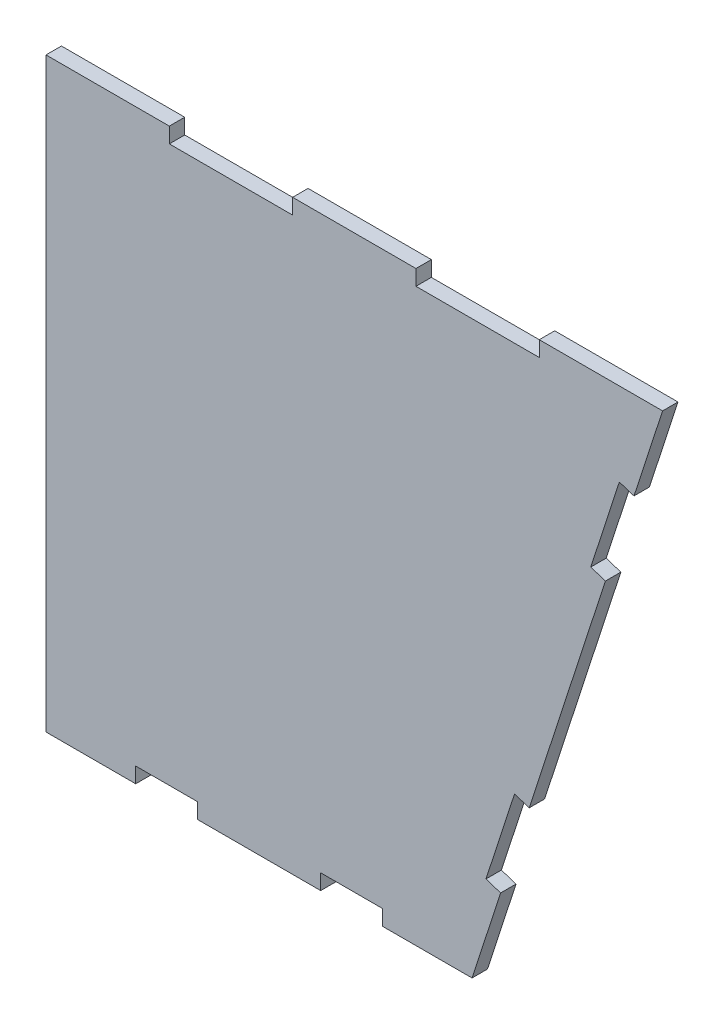
SolidWorks part; units mm, degrees
ref_plane "Front Plane" through (0, 0, 0) normal (0, 0, 1) x (1, 0, 0)
ref_plane "Top Plane" through (0, 0, 0) normal (0, 1, 0) x (1, 0, 0)
ref_plane "Right Plane" through (0, 0, 0) normal (1, 0, 0) x (0, 0, -1)
sketch "Sketch1" plane through (0, 0, 0) normal (0, 0, 1) x (1, 0, 0)
  line L0 (0, 0) -> (5.8868, 18.1176)
  line L1 (39.2452, 120.7842) -> (13.8452, 120.7842)
  line L2 (-87.7548, 120.7842) -> (-87.7548, 0)
  line L3 (-87.7548, 0) -> (-69.2774, 0)
  line L4 (33.3584, 102.6666) -> (30.3388, 103.6477)
  line L5 (30.3388, 103.6477) -> (24.452, 85.5301)
  line L6 (24.452, 85.5301) -> (27.4716, 84.5489)
  line L7 (19.6226, 60.3921) -> (-40.3388, 79.8747) construction
  line L8 (33.3584, 102.6666) -> (39.2452, 120.7842)
  line L9 (8.7539, 37.2164) -> (11.7735, 36.2353)
  line L10 (2.8672, 19.0988) -> (8.7539, 37.2164)
  line L11 (5.8868, 18.1176) -> (2.8672, 19.0988)
  line L12 (11.7735, 36.2353) -> (27.4716, 84.5489)
  line L13 (-24.2548, 120.7842) -> (-24.2548, 85.5301) construction
  line L14 (-87.7548, 60.3921) -> (-47.3707, 60.3921) construction
  line L15 (-43.8774, -0.5899) -> (-43.8774, 24.117) construction
  line L16 (-62.3548, 120.7842) -> (-62.3548, 117.6092)
  line L17 (-62.3548, 117.6092) -> (-36.9548, 117.6092)
  line L18 (-36.9548, 117.6092) -> (-36.9548, 120.7842)
  line L19 (-62.3548, 120.7842) -> (-87.7548, 120.7842)
  line L20 (-87.7548, 126.9801) -> (39.2452, 126.9801) construction
  line L21 (13.8452, 120.7842) -> (13.8452, 117.6092)
  line L22 (13.8452, 117.6092) -> (-11.5548, 117.6092)
  line L23 (-11.5548, 117.6092) -> (-11.5548, 120.7842)
  line L24 (-11.5548, 120.7842) -> (-36.9548, 120.7842)
  line L25 (-69.2774, 0) -> (-69.2774, 3.175)
  line L26 (-69.2774, 3.175) -> (-56.5774, 3.175)
  line L27 (-56.5774, 3.175) -> (-56.5774, 0)
  line L28 (-56.5774, 0) -> (-31.1774, 0)
  line L29 (-18.4774, 0) -> (-18.4774, 3.175)
  line L30 (-18.4774, 3.175) -> (-31.1774, 3.175)
  line L31 (-31.1774, 3.175) -> (-31.1774, 0)
  line L32 (-18.4774, 0) -> (0, 0)
  point P27 (-24.2548, 126.9801)
  point P40 (0, 0)
  dimension "D1" = 108
  dimension "D2" = 127
  dimension "D3" = 127
  dimension "D4" = 25.4
  dimension "D5" = 19.05
  dimension "D6" = 3.175
  dimension "D7" = 3.175
  dimension "D8" = 25.4
  dimension "D9" = 12.7
  dimension "D10" = 3.175
  dimension "D11" = 12.7
  dimension "D12" = 12.7
extrude "Boss-Extrude1" add sketch "Sketch1" along normal blind 3.175
